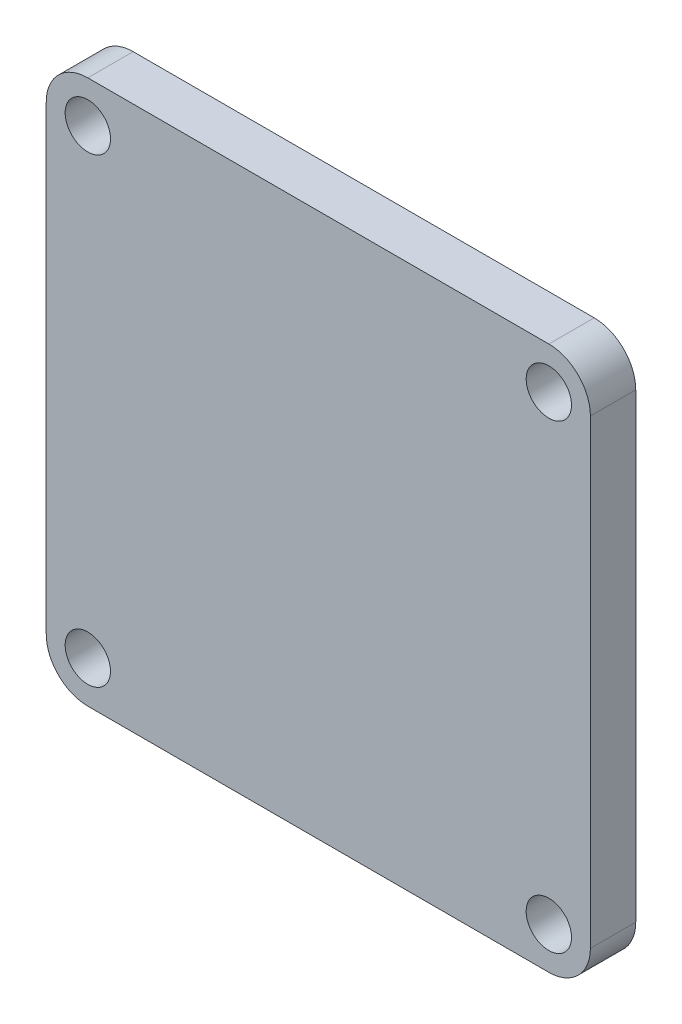
SolidWorks part; units mm, degrees
ref_plane "前视基准面" through (0, 0, 0) normal (0, 0, 1) x (1, 0, 0)
ref_plane "上视基准面" through (0, 0, 0) normal (0, 1, 0) x (1, 0, 0)
ref_plane "右视基准面" through (0, 0, 0) normal (1, 0, 0) x (0, 0, -1)
sketch "草图1" plane through (0, 0, 0) normal (0, 0, 1) x (1, 0, 0)
  line L0 (0, 18) -> (0, -18) construction
  line L1 (-15.25, 18) -> (15.25, 18)
  line L2 (-18, 15.25) -> (-18, -15.25)
  line L3 (-15.25, -18) -> (15.25, -18)
  line L4 (18, 15.25) -> (18, -15.25)
  line L5 (-18, 18) -> (18, -18) construction
  line L6 (-18, -18) -> (18, 18) construction
  line L7 (-18, 0) -> (18, 0) construction
  circle A0 centre (-15.25, 15.25) radius 1.5
  circle A1 centre (15.25, 15.25) radius 1.5
  circle A2 centre (15.25, -15.25) radius 1.5
  circle A3 centre (-15.25, -15.25) radius 1.5
  arc A4 (-15.25, -18) -> (-18, -15.25) centre (-15.25, -15.25) cw
  arc A5 (15.25, -18) -> (18, -15.25) centre (15.25, -15.25) ccw
  arc A6 (18, 15.25) -> (15.25, 18) centre (15.25, 15.25) ccw
  arc A7 (-18, 15.25) -> (-15.25, 18) centre (-15.25, 15.25) cw
  point P0 (0, 0)
  dimension "D1" = 3
  dimension "D2" = 30.5
  dimension "D5" = 2.75
  dimension "D3" = 36
  dimension "D4" = 36
extrude "凸台-拉伸1" add sketch "草图1" along normal blind 3
